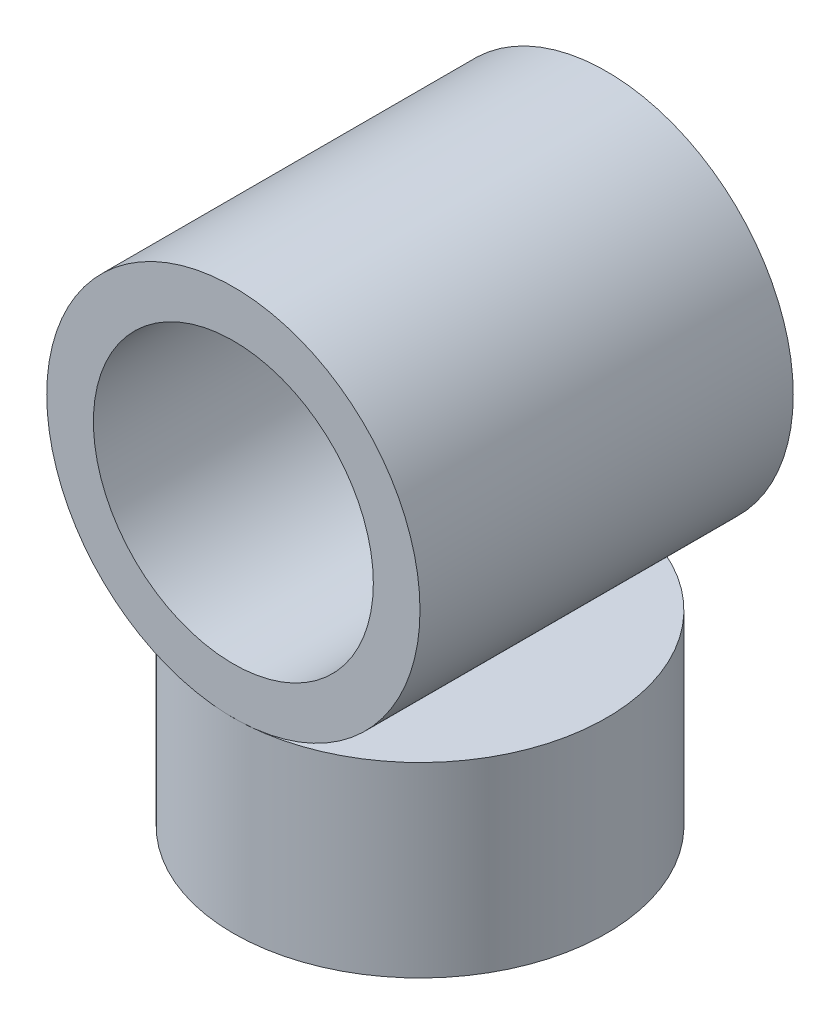
SolidWorks part; units mm, degrees
ref_plane "Front Plane" through (0, 0, 0) normal (0, 0, 1) x (1, 0, 0)
ref_plane "Top Plane" through (0, 0, 0) normal (0, 1, 0) x (1, 0, 0)
ref_plane "Right Plane" through (0, 0, 0) normal (1, 0, 0) x (0, 0, -1)
sketch "Sketch2" plane through (0, 0, 0) normal (0, 1, 0) x (1, 0, 0)
  circle A0 centre (0, 0) radius 10
  dimension "D1" = 20
extrude "Boss-Extrude2" add sketch "Sketch2" against normal blind 10
sketch "Sketch3" plane through (0, -10, 0) normal (0, -1, 0) x (-1, 0, 0)
  circle A0 centre (0, 0) radius 7.5
  dimension "D1" = 15
extrude "Cut-Extrude1" cut sketch "Sketch3" against normal blind 5
sketch "Sketch5" plane through (0, 0, 0) normal (0, 0, 1) x (1, 0, 0)
  circle A0 centre (0, 10) radius 10
  dimension "D2" = 20
  dimension "D1" = 10
extrude "Boss-Extrude3" add sketch "Sketch5" along normal mid plane 20 separate body
sketch "Sketch6" plane through (0, 0, 10) normal (0, 0, 1) x (1, 0, 0)
  circle A0 centre (0, 10) radius 7.5
  dimension "D1" = 15
extrude "Cut-Extrude2" cut sketch "Sketch6" against normal up to next (20 mm away)
